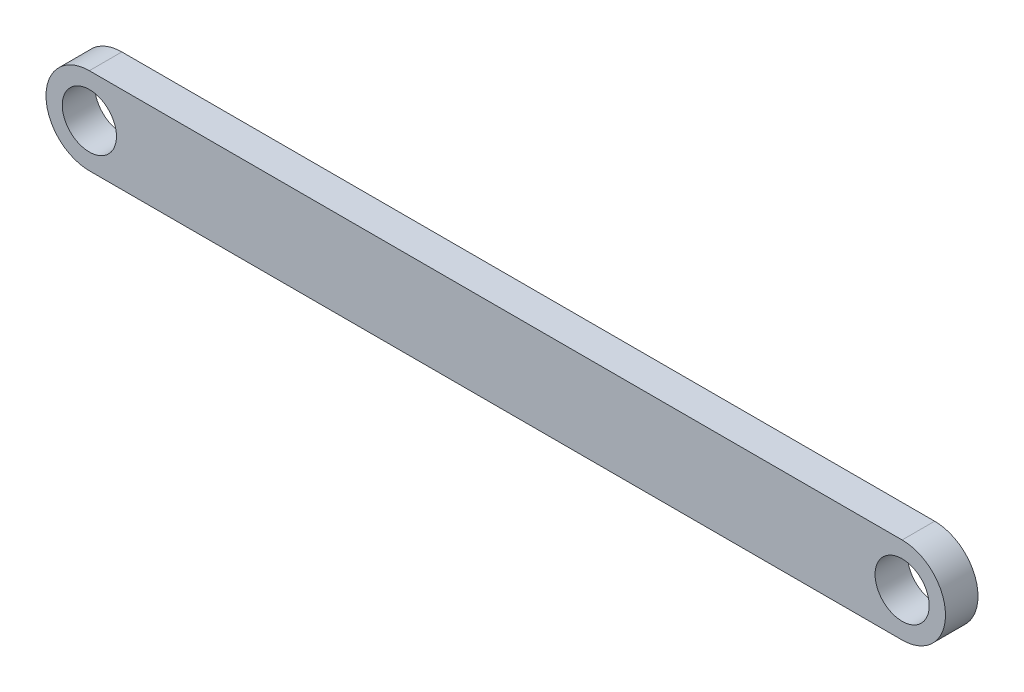
SolidWorks part; units mm, degrees
ref_plane "Front Plane" through (0, 0, 0) normal (0, 0, 1) x (1, 0, 0)
ref_plane "Top Plane" through (0, 0, 0) normal (0, 1, 0) x (1, 0, 0)
ref_plane "Right Plane" through (0, 0, 0) normal (1, 0, 0) x (0, 0, -1)
sketch "Sketch1" plane through (0, 34.7031, 0) normal (0, 0, 1) x (1, 0, 0)
  line L1 (-30.3724, 17.4326) -> (44.6276, 17.4326)
  line L3 (-30.3724, 9.4326) -> (44.6276, 9.4326)
  arc A0 (-30.3724, 17.4326) -> (-30.3724, 9.4326) centre (-30.3724, 13.4326) ccw
  arc A1 (44.6276, 17.4326) -> (44.6276, 9.4326) centre (44.6276, 13.4326) cw
  circle A2 centre (-30.3724, 13.4326) radius 2.5
  circle A3 centre (44.6276, 13.4326) radius 2.5
  dimension "D3" = 5
  dimension "D4" = 5
  dimension "D1" = 75
  dimension "D2" = 8
extrude "Boss-Extrude1" add sketch "Sketch1" along normal blind 3
